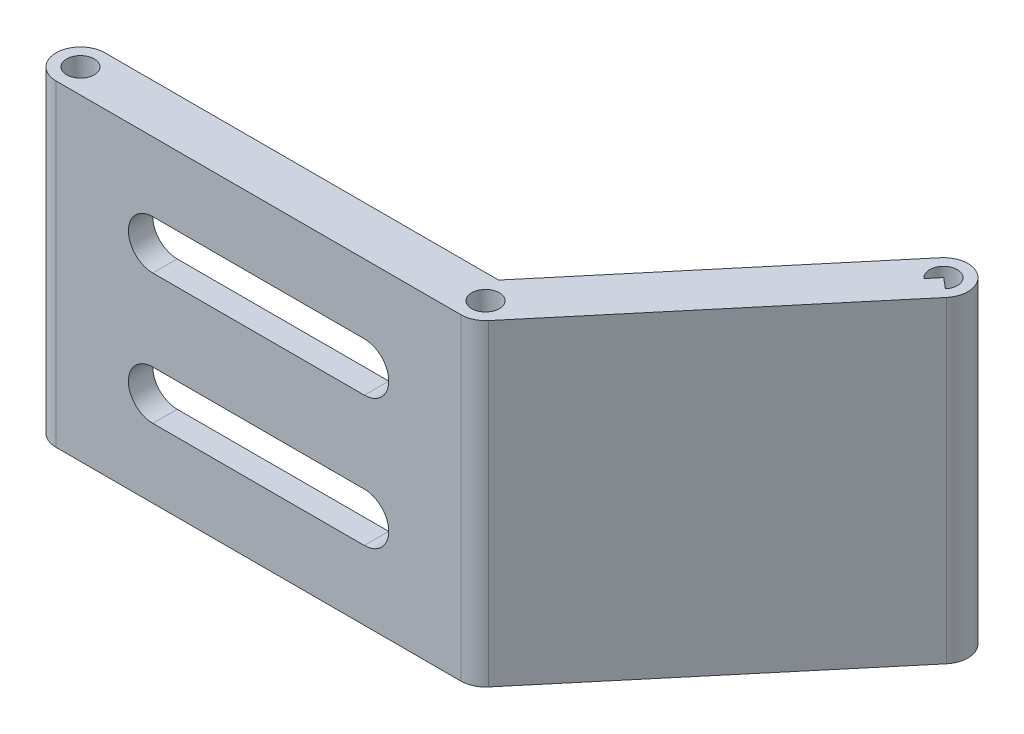
SolidWorks part; units mm, degrees
ref_plane "前视基准面" through (0, 0, 0) normal (0, 0, 1) x (1, 0, 0)
ref_plane "上视基准面" through (0, 0, 0) normal (0, 1, 0) x (1, 0, 0)
ref_plane "右视基准面" through (0, 0, 0) normal (1, 0, 0) x (0, 0, -1)
sketch "草图1" plane through (0, 0, 0) normal (0, 1, 0) x (1, 0, 0)
  line L0 (-24.2143, 0) -> (33.9857, 0) construction
  line L1 (0, 21.7286) -> (0, -22.0714) construction
  line L2 (-14.2777, -3) -> (35.5055, -3)
  line L5 (-11.2777, 0) -> (32.5055, 0)
  line L6 (35.5055, 0) -> (70.0693, 41.1916) construction
  line L7 (37.8036, -1.9284) -> (63.497, 28.6919)
  line L8 (37.4338, 2.2981) -> (61.1989, 30.6202)
  line L9 (61.1989, 30.6202) -> (63.497, 28.6919)
  line L10 (62.5642, 32.2474) -> (14.9363, -24.5134) construction
  line L11 (-14.2777, 0) -> (14.9363, -24.5134) construction
  circle A6 centre (-14.2777, 0) radius 1.7
  circle A7 centre (35.5055, 0) radius 1.7
  arc A8 (-11.2777, 0) -> (-14.2777, -3) centre (-14.2777, 0) ccw
  arc A9 (35.5055, -3) -> (37.8036, -1.9284) centre (35.5055, 0) ccw
  arc A11 (37.4338, 2.2981) -> (32.5055, 0) centre (35.5055, 0) ccw
  arc A12 (37.8036, -1.9284) -> (37.4338, 2.2981) centre (35.5055, 0) ccw construction
  dimension "D1" = 3.4
  dimension "D2" = 3.4
  dimension "D3" = 6
  dimension "D4" = 6
  dimension "D5" = 32
  dimension "D6" = 50
  dimension "D7" = 30.6202
extrude "凸台-拉伸1" add sketch "草图1" along normal blind 39
fillet "圆角1" radius 10 3 edges at (37.4338, 19.5, -2.2981) (32.5055, 19.5, 0) (-11.2777, 19.5, 0)
sketch "草图3" plane through (0, 0, 0) normal (0, 1, 0) x (1, 0, 0)
  line L0 (-14.2777, 0) -> (35.5055, 0) construction
  line L1 (-14.2777, 3) -> (35.5055, 3)
  line L2 (-14.2777, -3) -> (35.5055, -3)
  arc A0 (-14.2777, 3) -> (-14.2777, -3) centre (-14.2777, 0) ccw
  arc A1 (35.5055, -3) -> (35.5055, 3) centre (35.5055, 0) ccw
  point P4 (10.6139, 0)
  point P9 (0, 0)
  point P12 (0, 0)
  dimension "D1" = 3
extrude "凸台-拉伸2" add sketch "草图3" along normal blind 5
sketch "草图4" plane through (0, 39, 0) normal (0, 1, 0) x (1, 0, 0)
  line L0 (-14.2777, 0) -> (35.5055, 0) construction
  line L1 (-14.2777, 3) -> (35.5055, 3)
  line L2 (-14.2777, -3) -> (35.5055, -3)
  arc A0 (-14.2777, 3) -> (-14.2777, -3) centre (-14.2777, 0) ccw
  arc A1 (35.5055, -3) -> (35.5055, 3) centre (35.5055, 0) ccw
  circle A2 centre (-14.2777, 0) radius 1.7
  circle A3 centre (35.5055, 0) radius 1.7
  point P4 (10.6139, 0)
  dimension "D1" = 3
extrude "凸台-拉伸3" add sketch "草图4" against normal blind 3
sketch "草图5" plane through (0, 0, 3) normal (0, 0, 1) x (1, 0, 0)
  line L0 (-17.2777, 19.5) -> (37.8036, 19.5) construction
  line L1 (-17.2777, 39) -> (-17.2777, 0) construction
  line L2 (37.8036, 39) -> (37.8036, 0) construction
  line L3 (10.6139, 39) -> (10.6139, 0) construction
  line L4 (-14.2777, 39) -> (35.5055, 39) construction
  line L5 (-14.2777, 0) -> (35.5055, 0) construction
  line L6 (-2.3861, 27.5) -> (23.6139, 27.5) construction
  line L7 (-2.3861, 30.5) -> (23.6139, 30.5)
  line L8 (-2.3861, 24.5) -> (23.6139, 24.5)
  line L9 (-2.3861, 11.5) -> (23.6139, 11.5) construction
  line L10 (-2.3861, 8.5) -> (23.6139, 8.5)
  line L11 (-2.3861, 14.5) -> (23.6139, 14.5)
  arc A0 (-2.3861, 30.5) -> (-2.3861, 24.5) centre (-2.3861, 27.5) ccw
  arc A1 (23.6139, 24.5) -> (23.6139, 30.5) centre (23.6139, 27.5) ccw
  arc A2 (-2.3861, 8.5) -> (-2.3861, 14.5) centre (-2.3861, 11.5) cw
  arc A3 (23.6139, 14.5) -> (23.6139, 8.5) centre (23.6139, 11.5) cw
  point P14 (10.6139, 27.5)
  point P21 (10.6139, 11.5)
  point P26 (11.3094, 27.5)
  dimension "D1" = 3
  dimension "D2" = 26
  dimension "D3" = 8
extrude "切除-拉伸2" cut sketch "草图5" against normal blind 5
sketch "草图6" plane through (0, 39, 0) normal (0, 1, 0) x (1, 0, 0)
  line L0 (35.5055, 0) -> (61.1885, 30.6079) construction
  line L1 (61.1989, 30.6202) -> (40.8449, 6.3632) construction
  line L2 (35.5055, 0) -> (61.1885, 30.6079) construction
  line L3 (33.2073, 1.9284) -> (58.8904, 32.5362)
  line L4 (37.8036, -1.9284) -> (63.4867, 28.6795)
  arc A0 (33.2073, 1.9284) -> (37.8036, -1.9284) centre (35.5055, 0) ccw
  arc A1 (63.4867, 28.6795) -> (58.8904, 32.5362) centre (61.1885, 30.6079) ccw
  circle A2 centre (35.5055, 0) radius 1.7
  circle A3 centre (61.1885, 30.6079) radius 1.7
  point P7 (48.347, 15.3039)
  point P14 (64.123, 34.1067)
  point P15 (62.8502, 32.5898)
  point P18 (61.1878, 30.6085)
  dimension "D1" = 3
  dimension "D2" = 3.4
extrude "凸台-拉伸4" add sketch "草图6" against normal blind 3
sketch "草图7" plane through (0, 0, 0) normal (0, 1, 0) x (1, 0, 0)
  line L0 (35.5055, 0) -> (61.1885, 30.6079) construction
  line L1 (33.2073, 1.9284) -> (58.8904, 32.5362)
  line L2 (37.8036, -1.9284) -> (63.4867, 28.6795)
  arc A0 (33.2073, 1.9284) -> (37.8036, -1.9284) centre (35.5055, 0) ccw
  arc A1 (63.4867, 28.6795) -> (58.8904, 32.5362) centre (61.1885, 30.6079) ccw
  circle A2 centre (35.5055, 0) radius 1.7
  circle A3 centre (61.1885, 30.6079) radius 1.7
  point P4 (48.347, 15.3039)
  dimension "D1" = 3
extrude "凸台-拉伸5" add sketch "草图7" along normal blind 5
sketch "草图8" plane through (0, 0, 0) normal (0, 1, 0) x (1, 0, 0)
  circle A0 centre (61.1885, 30.6079) radius 3
  circle A1 centre (61.1885, 30.6079) radius 1.7
extrude "凸台-拉伸6" add sketch "草图8" along normal blind 39
sketch "草图9" plane through (0, 0, 0) normal (0, 1, 0) x (1, 0, 0)
  circle A0 centre (61.1885, 30.6079) radius 1.7
